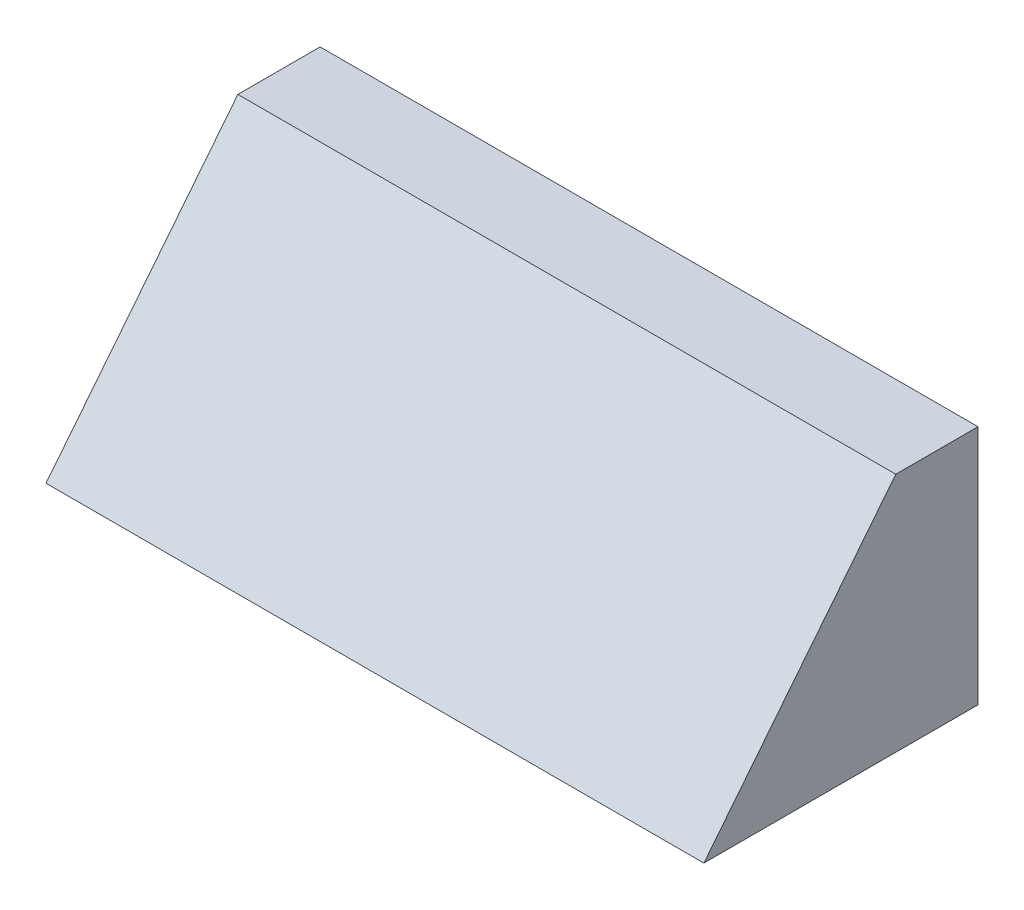
SolidWorks part; units mm, degrees
ref_plane "前基準面" through (0, 0, 0) normal (0, 0, 1) x (1, 0, 0)
ref_plane "上基準面" through (0, 0, 0) normal (0, 1, 0) x (1, 0, 0)
ref_plane "右基準面" through (0, 0, 0) normal (1, 0, 0) x (0, 0, -1)
sketch "草圖1" plane through (0, 0, 0) normal (1, 0, 0) x (0, 0, -1)
  line L0 (10, 8.7857) -> (4, 8.7857)
  line L1 (-10, -8.7857) -> (10, -8.7857)
  line L4 (10, -8.7857) -> (10, 8.7857)
  line L5 (0, 8.7857) -> (0, -8.7857) construction
  line L6 (-12, 0) -> (10, 0) construction
  line L7 (-10, -8.7857) -> (4, 8.7857)
  point P0 (0, 0)
  dimension "D1" = 6
  dimension "D2" = 20
extrude "填料-伸長1" add sketch "草圖1" along normal blind 48
